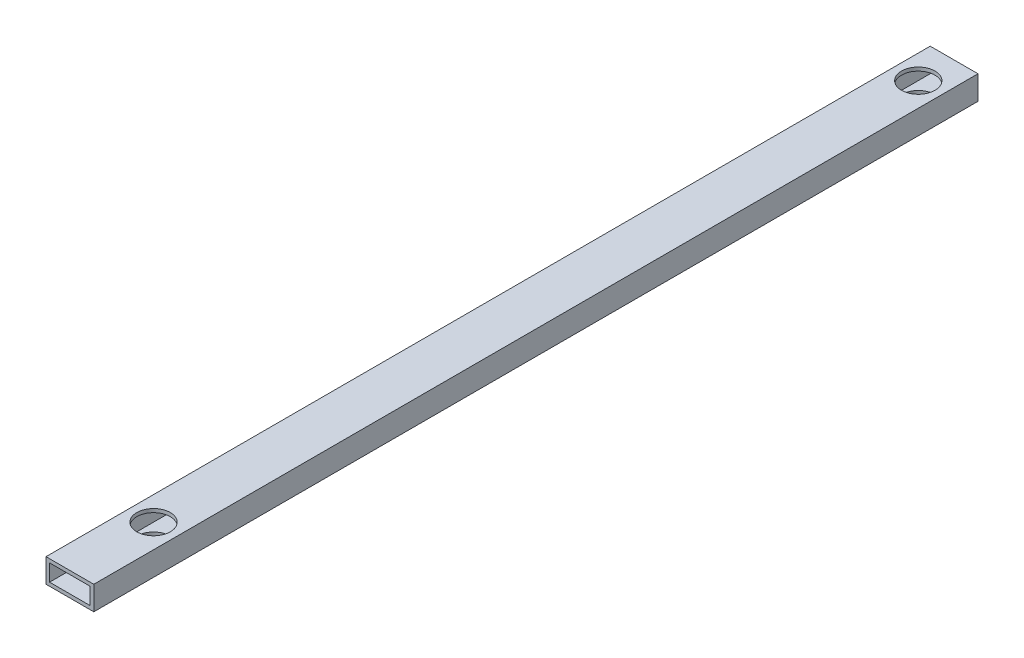
SolidWorks part; units mm, degrees
material "6061 合金"
ref_plane "前视基准面" through (0, 0, 0) normal (0, 0, 1) x (1, 0, 0)
ref_plane "上视基准面" through (0, 0, 0) normal (0, 1, 0) x (1, 0, 0)
ref_plane "右视基准面" through (0, 0, 0) normal (1, 0, 0) x (0, 0, -1)
sketch "草图1" plane through (0, 0, 0) normal (0, 0, 1) x (1, 0, 0)
  line L1 (-10, 5) -> (10, 5)
  line L2 (-10, 5) -> (-10, -5)
  line L3 (-10, -5) -> (10, -5)
  line L4 (10, 5) -> (10, -5)
  line L5 (-10, 5) -> (10, -5) construction
  line L6 (-10, -5) -> (10, 5) construction
  line L7 (-8.5, 3.5) -> (8.5, 3.5)
  line L8 (-8.5, 3.5) -> (-8.5, -3.5)
  line L9 (-8.5, -3.5) -> (8.5, -3.5)
  line L10 (8.5, 3.5) -> (8.5, -3.5)
  line L11 (-8.5, 3.5) -> (8.5, -3.5) construction
  line L12 (-8.5, -3.5) -> (8.5, 3.5) construction
  point P0 (0, 0)
  point P5 (0, 0)
  dimension "D1" = 20
  dimension "D2" = 10
  dimension "D3" = 17
  dimension "D4" = 7
extrude "凸台-拉伸1" add sketch "草图1" along normal blind 370
sketch "草图2" plane through (0, 5, 0) normal (0, 1, 0) x (1, 0, 0)
  line L0 (0, -55) -> (0, 55) construction
  circle A0 centre (0, -15) radius 7
  circle A1 centre (0, -335) radius 7
  dimension "D1" = 15
  dimension "D2" = 320
  dimension "D3" = 14
extrude "切除-拉伸1" cut sketch "草图2" against normal blind 280
